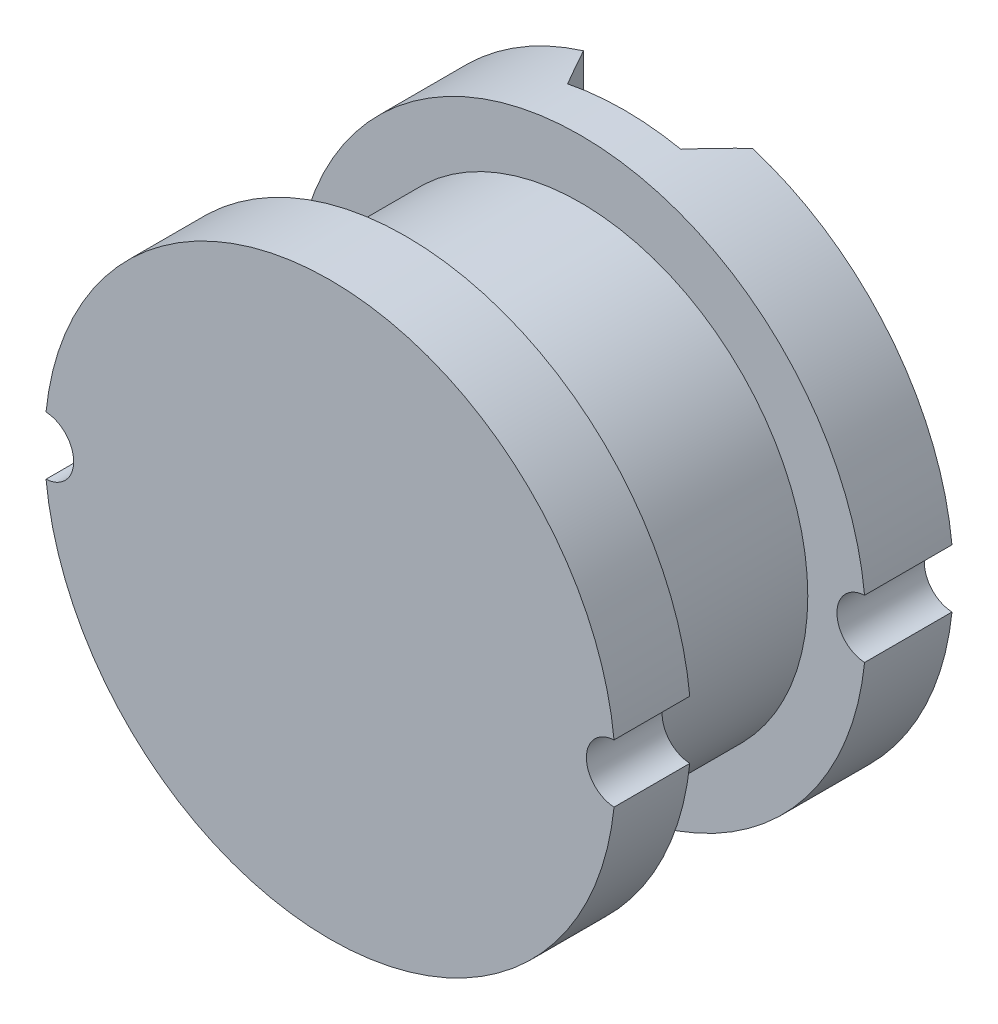
SolidWorks part; units mm, degrees
ref_plane "Спереди" through (0, 0, 0) normal (0, 0, 1) x (1, 0, 0)
ref_plane "Сверху" through (0, 0, 0) normal (0, 1, 0) x (1, 0, 0)
ref_plane "Справа" through (0, 0, 0) normal (1, 0, 0) x (0, 0, -1)
sketch "Эскиз1" plane through (0, 0, 0) normal (0, 0, 1) x (1, 0, 0)
  circle A0 centre (0, 0) radius 4.9
extrude "Бобышка-Вытянуть1" add sketch "Эскиз1" along normal blind 1.5
sketch "Эскиз3" plane through (0, 0, 1.5) normal (0, 0, 1) x (1, 0, 0)
  circle A0 centre (0, 0) radius 3.9
extrude "Бобышка-Вытянуть2" add sketch "Эскиз3" along normal blind 3
sketch "Эскиз4" plane through (0, 0, 4.5) normal (0, 0, 1) x (1, 0, 0)
  circle A0 centre (0, 0) radius 4.9
extrude "Бобышка-Вытянуть3" add sketch "Эскиз4" along normal blind 1.3
sketch "Эскиз5" plane through (0, 0, 0) normal (0, 1, 0) x (1, 0, 0)
  line L0 (1.45, 0) -> (0.972, -0.75)
  line L2 (-1.45, 0) -> (-1.45, 0.521)
  line L3 (-1.45, 0) -> (-0.972, -0.75)
  line L4 (-1.45, 0.521) -> (1.45, 0.521)
  line L5 (0.972, -0.75) -> (-0.972, -0.75)
  line L6 (1.45, 0.521) -> (1.45, 0)
extrude "Вырез-Вытянуть1" cut sketch "Эскиз5" against normal through all both and the other way through all
sketch "Эскиз6" plane through (0, 0, 5.8) normal (0, 0, 1) x (1, 0, 0)
  circle A0 centre (-4.9, 0) radius 0.5
  circle A1 centre (0, 0) radius 4.9 construction
  circle A2 centre (4.9, 0) radius 0.5
extrude "Вырез-Вытянуть2" cut sketch "Эскиз6" against normal through all
